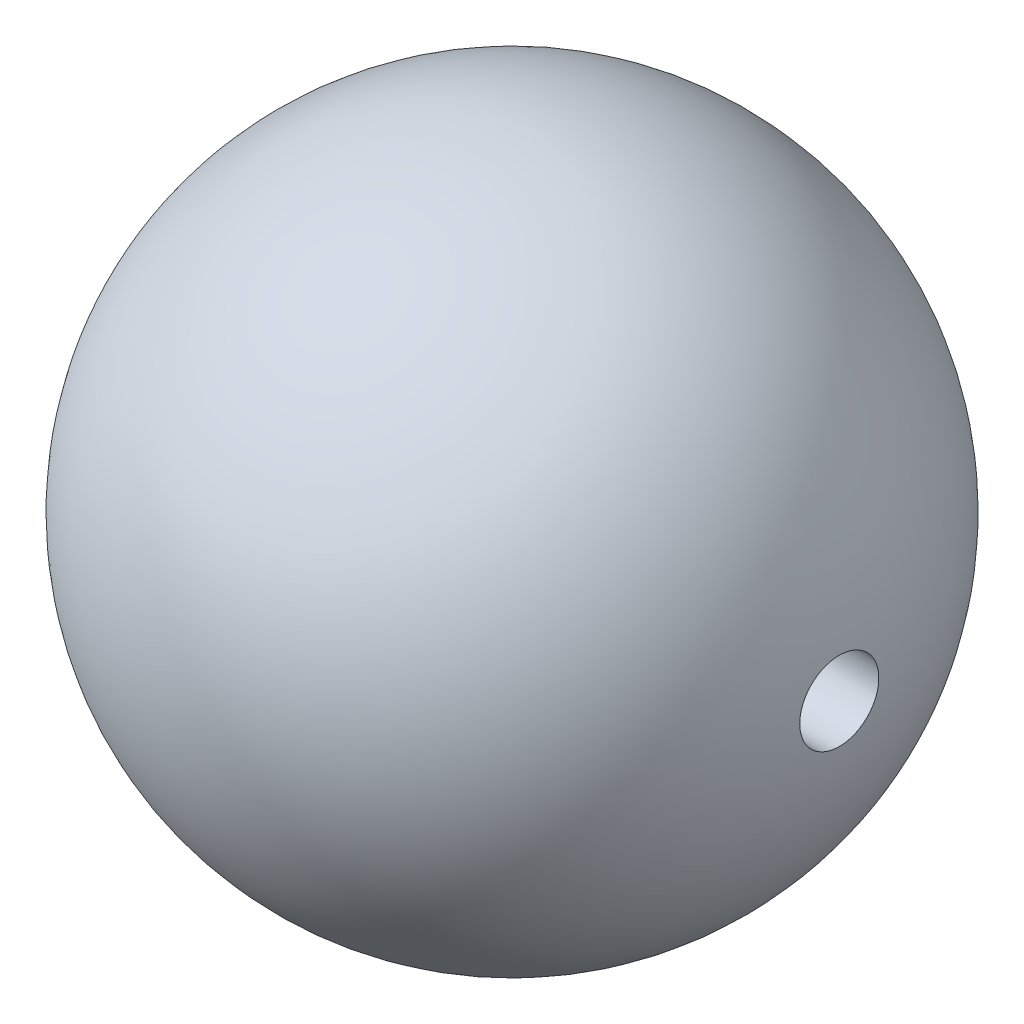
SolidWorks part; units mm, degrees
ref_plane "Front Plane" through (0, 0, 0) normal (0, 0, 1) x (1, 0, 0)
ref_plane "Top Plane" through (0, 0, 0) normal (0, 1, 0) x (1, 0, 0)
ref_plane "Right Plane" through (0, 0, 0) normal (1, 0, 0) x (0, 0, -1)
sketch "Sketch2" plane through (0, 0, 0) normal (0, 0, 1) x (1, 0, 0)
  line L0 (0, 12.5) -> (0, -12.5)
  arc A0 (0, 12.5) -> (0, -12.5) centre (0, 0) cw
  dimension "D1" = 25
revolve "Revolve1" add sketch "Sketch2" angle 360 about L0
sketch "Sketch3" plane through (0, 0, 0) normal (1, 0, 0) x (0, 0, -1)
  circle A0 centre (0, 0) radius 1.5
  dimension "D1" = 3
extrude "Cut-Extrude1" cut sketch "Sketch3" against normal through all both and the other way through all
